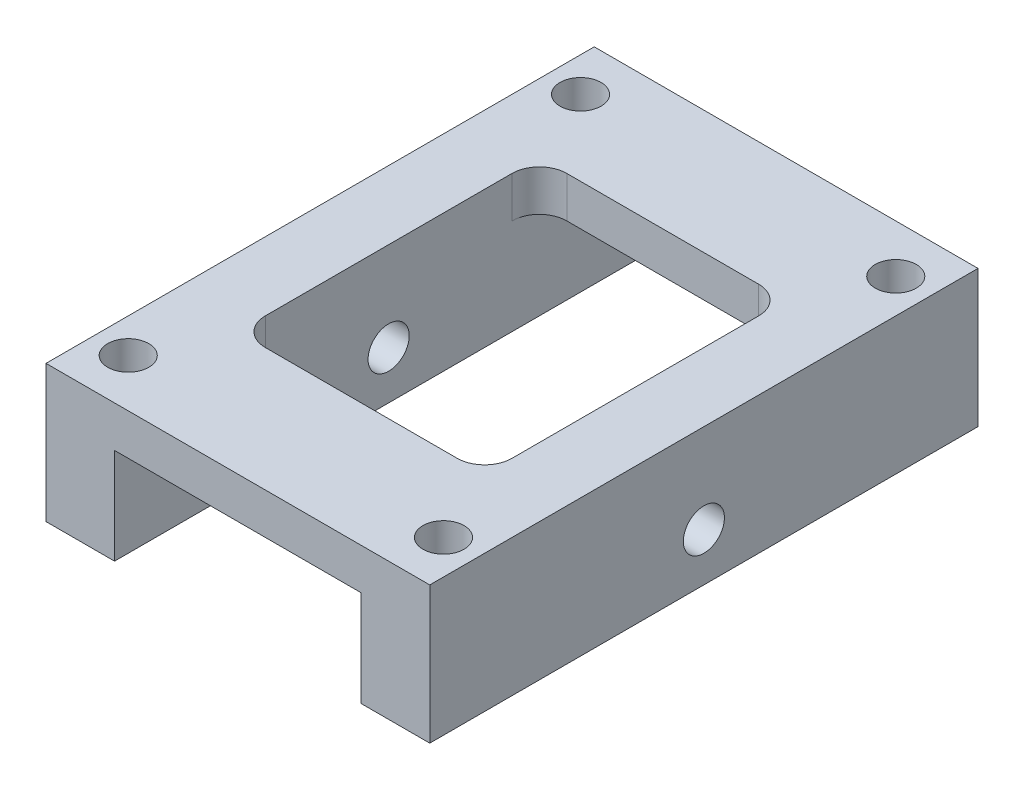
SolidWorks part; units mm, degrees
material "6061 合金"
ref_plane "前视基准面" through (0, 0, 0) normal (0, 0, 1) x (1, 0, 0)
ref_plane "上视基准面" through (0, 0, 0) normal (0, 1, 0) x (1, 0, 0)
ref_plane "右视基准面" through (0, 0, 0) normal (1, 0, 0) x (0, 0, -1)
sketch "草图1" plane through (0, 0, 0) normal (0, 0, 1) x (1, 0, 0)
  line L0 (0, 0) -> (0, 10)
  line L1 (0, 10) -> (28, 10)
  line L2 (28, 10) -> (28, 0)
  line L3 (28, 0) -> (23, 0)
  line L4 (23, 0) -> (23, 7)
  line L5 (23, 7) -> (5, 7)
  line L6 (5, 7) -> (5, 0)
  line L7 (5, 0) -> (0, 0)
  dimension "D1" = 10
  dimension "D2" = 28
  dimension "D3" = 5
  dimension "D4" = 7
extrude "凸台-拉伸1" add sketch "草图1" along normal blind 40
sketch "草图2" plane through (0, 10, 0) normal (0, 1, 0) x (1, 0, 0)
  line L0 (28, -40) -> (0, -40) construction
  line L1 (2.5, -3.5) -> (25.5, -3.5) construction
  line L2 (2.5, -3.5) -> (2.5, -36.5) construction
  line L3 (2.5, -36.5) -> (25.5, -36.5) construction
  line L4 (25.5, -3.5) -> (25.5, -36.5) construction
  line L5 (0, -40) -> (0, 0) construction
  circle A0 centre (2.5, -3.5) radius 1.5
  circle A1 centre (2.5, -36.5) radius 1.5
  circle A2 centre (25.5, -36.5) radius 1.5
  circle A3 centre (25.5, -3.5) radius 1.5
  dimension "D5" = 3
  dimension "D6" = 3
  dimension "D7" = 3
  dimension "D8" = 3
  dimension "D1" = 33
  dimension "D2" = 23
  dimension "D3" = 3.5
  dimension "D4" = 2.5
extrude "切除-拉伸1" cut sketch "草图2" against normal blind 40
sketch "草图3" plane through (0, 0, 0) normal (-1, 0, 0) x (0, 0, 1)
  line L0 (40, 0) -> (0, 0) construction
  line L1 (40, 10) -> (40, 0) construction
  circle A0 centre (20, 3.5) radius 1.5
  dimension "D1" = 3
  dimension "D2" = 3.5
  dimension "D3" = 20
extrude "切除-拉伸2" cut sketch "草图3" against normal blind 40
sketch "草图5" plane through (0, 10, 0) normal (0, 1, 0) x (1, 0, 0)
  line L0 (14, -40) -> (14, -31) construction
  line L2 (28, -40) -> (0, -40) construction
  line L4 (14, -31) -> (14, -20) construction
  line L9 (5, -31) -> (23, -31)
  line L10 (5, -31) -> (5, -9)
  line L11 (5, -9) -> (23, -9)
  line L12 (23, -31) -> (23, -9)
  line L13 (5, -31) -> (23, -9) construction
  line L14 (5, -9) -> (23, -31) construction
  dimension "D1" = 9
  dimension "D2" = 11
  dimension "D3" = 22
  dimension "D4" = 18
extrude "切除-拉伸3" cut sketch "草图5" against normal through all
fillet "圆角3" radius 2 4 edges at (5, 8.5, 31) (23, 8.5, 31) (5, 8.5, 9) (23, 8.5, 9)
